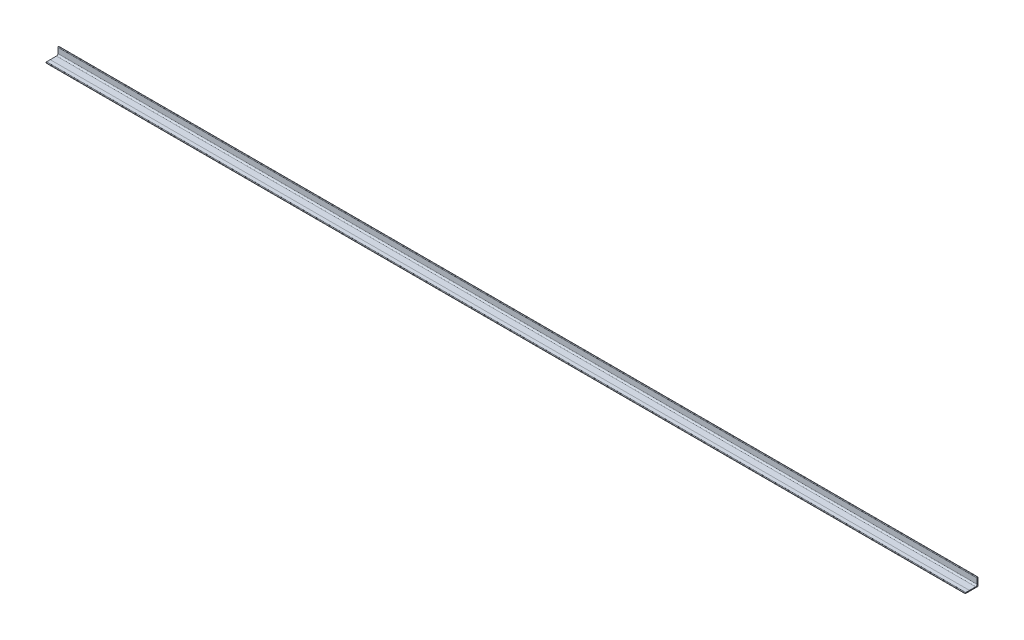
SolidWorks part; units mm, degrees
ref_plane "Front Plane" through (0, 0, 0) normal (0, 0, 1) x (1, 0, 0)
ref_plane "Top Plane" through (0, 0, 0) normal (0, 1, 0) x (1, 0, 0)
ref_plane "Right Plane" through (0, 0, 0) normal (1, 0, 0) x (0, 0, -1)
sketch "Sketch1" plane through (0, 0, 0) normal (0, 0, 1) x (1, 0, 0)
  line L0 (0, 0) -> (5060, 0)
  dimension "D1" = 5060
other "Angle iron 70X45X4.5(1)"
ref_plane "Plane1" through (0, 0, 0) normal (1, 0, 0) x (0, 1, 0)
sketch "Sketch11" plane through (0, 0, 0) normal (1, 0, 0) x (0, 1, 0)
  line L0 (0, 0) -> (0, 70)
  line L1 (0, 0) -> (45, 0)
  line L2 (4.5, 12.5) -> (4.5, 67)
  line L3 (12.5, 4.5) -> (42, 4.5)
  line L4 (0, 70) -> (1.5, 70)
  line L5 (45, 0) -> (45, 1.5)
  line L6 (4.5, 4.5) -> (45, 4.5) construction
  line L7 (4.5, 4.5) -> (4.5, 70) construction
  arc A0 (12.5, 4.5) -> (4.5, 12.5) centre (12.5, 12.5) cw
  arc A1 (45, 1.5) -> (42, 4.5) centre (42, 1.5) ccw
  arc A2 (4.5, 67) -> (1.5, 70) centre (1.5, 67) ccw
  point P2 (0, 0)
  dimension "D4" = 8
  dimension "D5" = 3
  dimension "D1" = 70
  dimension "D2" = 45
  dimension "D3" = 4.5
sketch "Sketch12" plane through (0, 4.5, 0) normal (0, 1, 0) x (1, 0, 0)
  line L0 (5060, -12.5) -> (5060, -67) construction
  line L1 (0, -67) -> (5060, -67)
  line L2 (0, -67) -> (0, -47)
  line L3 (0, -47) -> (5060, -47)
  line L4 (5060, -67) -> (5060, -47)
  dimension "D1" = 20
extrude "Boss-Extrude1" add sketch "Sketch12" along normal blind 0.1 separate body
